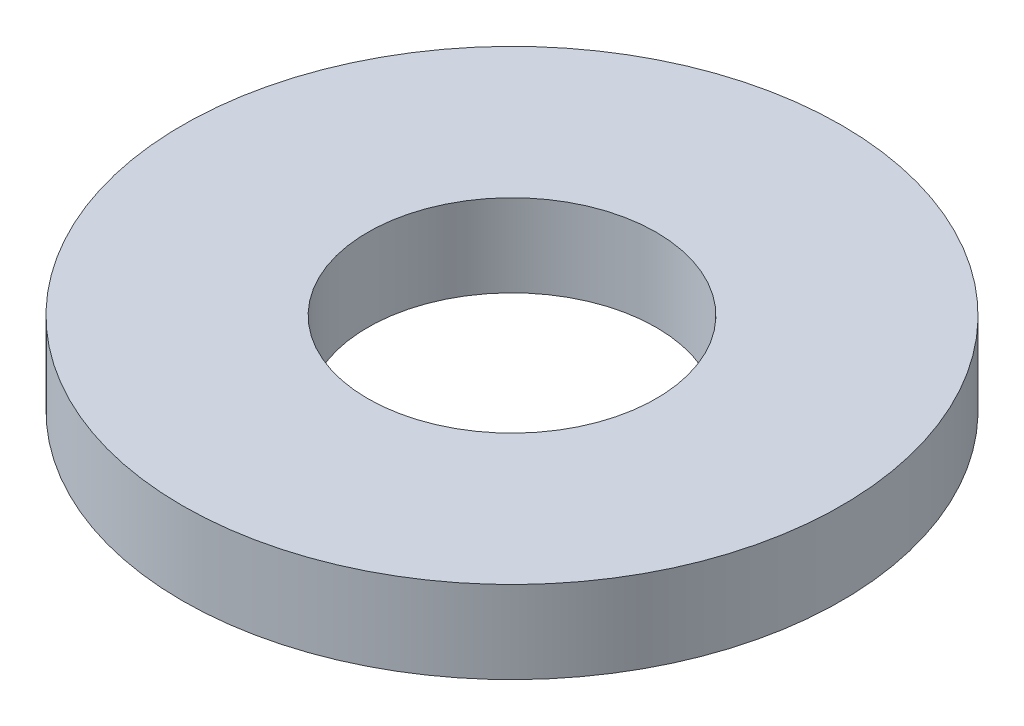
SolidWorks part; units mm, degrees
ref_plane "前视基准面" through (0, 0, 0) normal (0, 0, 1) x (1, 0, 0)
ref_plane "上视基准面" through (0, 0, 0) normal (0, 1, 0) x (1, 0, 0)
ref_plane "右视基准面" through (0, 0, 0) normal (1, 0, 0) x (0, 0, -1)
other "Configuration Table"
sketch "草图1" plane through (0, 0, 0) normal (0, 1, 0) x (1, 0, 0)
  circle A0 centre (0, 0) radius 4
  circle A1 centre (0, 0) radius 1.75
  dimension "D1" = 3.5
  dimension "D2" = 8
extrude "凸台-拉伸1" add sketch "草图1" along normal blind 1
